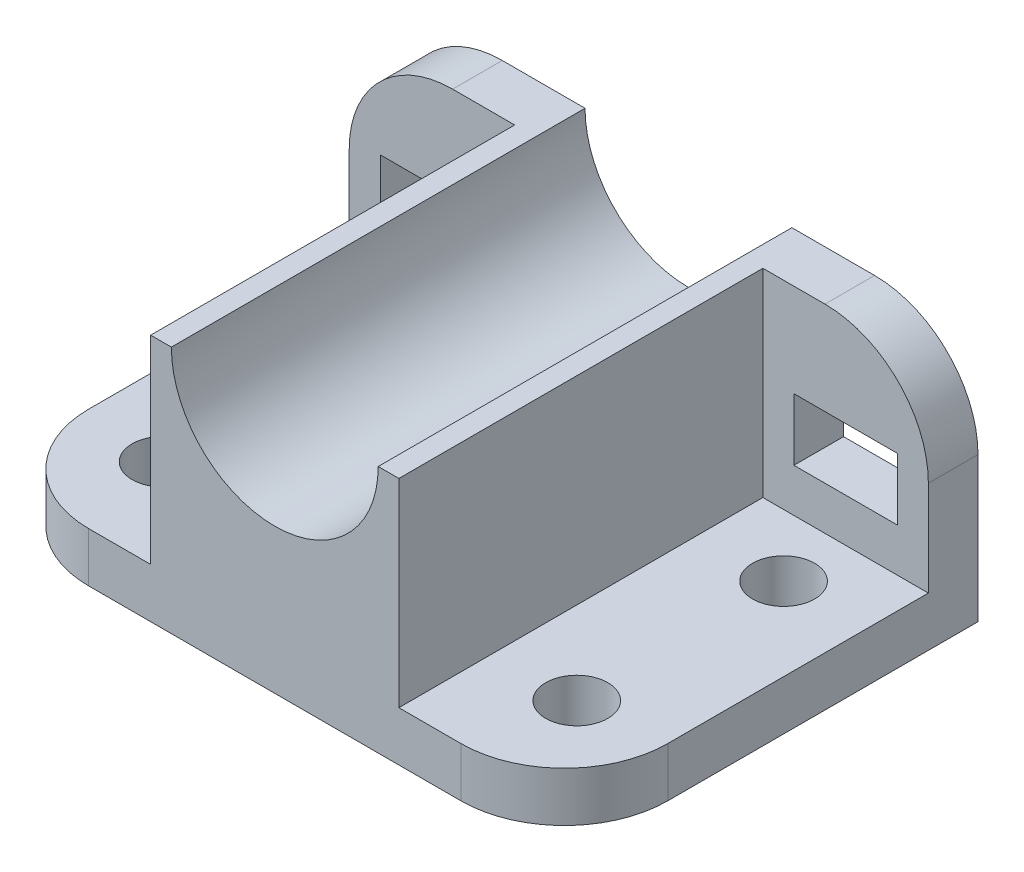
SolidWorks part; units mm, degrees
ref_plane "Front Plane" through (0, 0, 0) normal (0, 0, 1) x (1, 0, 0)
ref_plane "Top Plane" through (0, 0, 0) normal (0, 1, 0) x (1, 0, 0)
ref_plane "Right Plane" through (0, 0, 0) normal (1, 0, 0) x (0, 0, -1)
sketch "Sketch2" plane through (0, 0, 0) normal (0, 0, 1) x (1, 0, 0)
  line L0 (-70, 0) -> (70, 0)
  line L1 (70, 0) -> (70, 60)
  line L2 (70, 60) -> (25, 60)
  line L3 (-70, 60) -> (-70, 0)
  line L4 (-25, 60) -> (-70, 60)
  line L5 (62.5, 22.5) -> (37.5, 22.5)
  line L6 (62.5, 22.5) -> (62.5, 37.5)
  line L7 (62.5, 37.5) -> (37.5, 37.5)
  line L8 (37.5, 22.5) -> (37.5, 37.5)
  line L9 (62.5, 22.5) -> (37.5, 37.5) construction
  line L10 (62.5, 37.5) -> (37.5, 22.5) construction
  line L11 (-37.5, 22.5) -> (-62.5, 22.5)
  line L12 (-37.5, 22.5) -> (-37.5, 37.5)
  line L13 (-37.5, 37.5) -> (-62.5, 37.5)
  line L14 (-62.5, 22.5) -> (-62.5, 37.5)
  line L15 (-37.5, 22.5) -> (-62.5, 37.5) construction
  line L16 (-37.5, 37.5) -> (-62.5, 22.5) construction
  arc A0 (-25, 60) -> (25, 60) centre (0, 60) ccw
  point P2 (-50, 30)
  point P5 (0, 0)
  point P7 (50, 30)
  point P18 (0, 0)
  dimension "D8" = 25
  dimension "D1" = 60
  dimension "D2" = 140
  dimension "D3" = 7.5
  dimension "D4" = 15
  dimension "D5" = 25
  dimension "D6" = 22.5
  dimension "D7" = 7.5
  dimension "D9" = 45
extrude "Boss-Extrude1" add sketch "Sketch2" along normal blind 100
sketch "Sketch3" plane through (0, 0, 100) normal (0, 0, 1) x (1, 0, 0)
  line L0 (-70, 60) -> (-70, 0) construction
  line L1 (-70, 60) -> (-70, 0)
  line L2 (-70, 12) -> (-30, 12)
  line L3 (-30, 12) -> (-30, 60)
  line L4 (-25, 60) -> (-70, 60) construction
  line L5 (-30, 60) -> (-70, 60)
  line L6 (-70, 0) -> (70, 0) construction
  line L7 (0, 0) -> (0, 60) construction
  line L8 (30, 60) -> (70, 60)
  line L9 (30, 12) -> (30, 60)
  line L10 (70, 12) -> (30, 12)
  line M4 (-70, 60) -> (-70, 0)
  line M6 (70, 0) -> (70, 60)
  line M7 (70, 60) -> (25, 60)
  line M9 (-25, 60) -> (-70, 60)
  line M10 (62.5, 22.5) -> (37.5, 22.5)
  line M11 (37.5, 22.5) -> (37.5, 37.5)
  line M12 (37.5, 37.5) -> (62.5, 37.5)
  line M13 (62.5, 37.5) -> (62.5, 22.5)
  line M14 (-37.5, 22.5) -> (-62.5, 22.5)
  line M15 (-62.5, 22.5) -> (-62.5, 37.5)
  line M16 (-62.5, 37.5) -> (-37.5, 37.5)
  line M17 (-37.5, 37.5) -> (-37.5, 22.5)
  dimension "D1" = 12
  dimension "D2" = 5
extrude "Cut-Extrude1" cut sketch "Sketch3" against normal blind 88 contours L2 L3 M9 M4 M17 M14 M15 M16 | L10 L9 M6 M7 M13 M10 M11 M12
hole_wizard "Ø12.0mm Dowel Hole1" positions "Sketch4" profile "Sketch5" hole size "Ø12.0" standard "ANSI Metric" end condition through all
sketch "Sketch4" plane through (0, 12, 0) normal (0, 1, 0) x (1, 0, 0)
  line L0 (-25, 0) -> (-70, 0) construction
  line L1 (0, 0) -> (0, -100) construction
  line L2 (-25, -100) -> (25, -100) construction
  point P0 (-50, -27)
  point P2 (-50, -77)
  point P4 (50, -77)
  point P6 (50, -27)
  point P22 (0, 0)
  dimension "D1" = 27
  dimension "D2" = 50
  dimension "D3" = 100
sketch "Sketch5" plane through (-50, 12, 27) normal (1, 0, 0) x (0, 0, 1)
  line L0 (0, 0) -> (0, 12)
  line L1 (0, 12) -> (7.5, 12)
  line L2 (7.5, 12) -> (7.5, 0)
  line L5 (7.5, 0) -> (0, 0)
  line L11 (0, -6.35) -> (0, 107.95) construction
  dimension "Thru Hole Dia." = 15
  dimension "Thru Hole Depth" = 12
fillet "Fillet1" radius 25 4 edges at (70, 60, 6) (-70, 60, 6) (-70, 6, 100) (70, 6, 100)
